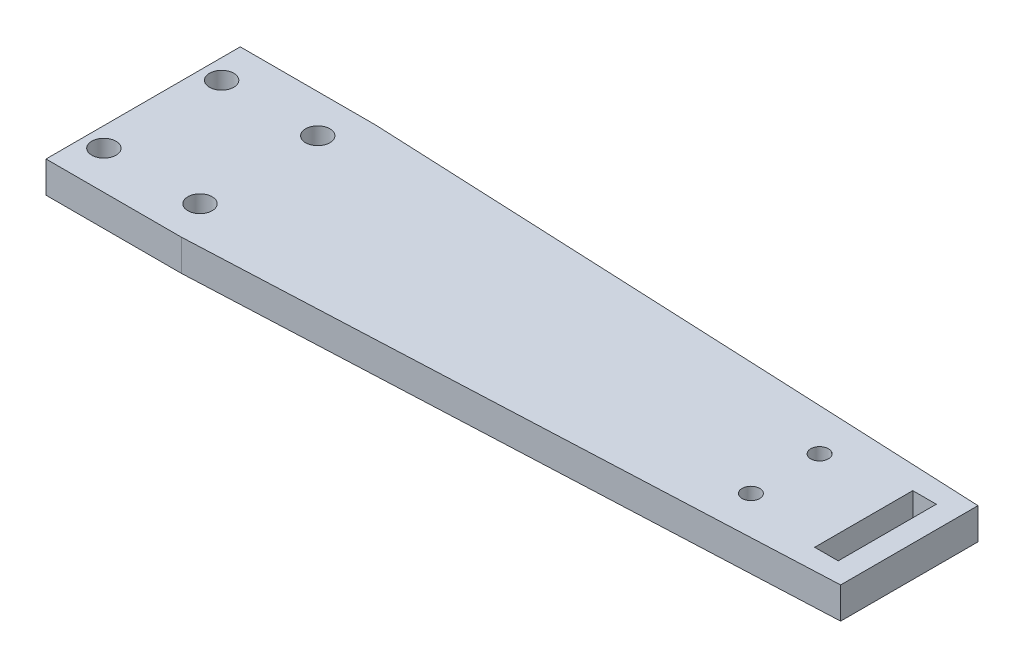
SolidWorks part; units mm, degrees
ref_plane "Front Plane" through (0, 0, 0) normal (0, 0, 1) x (1, 0, 0)
ref_plane "Top Plane" through (0, 0, 0) normal (0, 1, 0) x (1, 0, 0)
ref_plane "Right Plane" through (0, 0, 0) normal (1, 0, 0) x (0, 0, -1)
sketch "Sketch1" plane through (0, 0, 0) normal (0, 1, 0) x (1, 0, 0)
  line L1 (0, 0) -> (34.5, 0)
  line L2 (0, 0) -> (0, 49.5)
  line L3 (0, 49.5) -> (34.5, 49.5)
  line L4 (34.5, 0) -> (34.5, 49.5)
  dimension "D1" = 34.5
  dimension "D2" = 49.5
extrude "Boss-Extrude1" add sketch "Sketch1" along normal blind 8
sketch "Sketch2" plane through (0, 8, 0) normal (0, 1, 0) x (1, 0, 0)
  line L0 (34.5, 49.5) -> (0, 49.5) construction
  line L1 (0, 49.5) -> (0, 0) construction
  line L2 (17.25, 49.5) -> (17.25, 0) construction
  line L3 (0, 0) -> (34.5, 0) construction
  line L4 (0, 24.75) -> (17.25, 24.75) construction
  circle A0 centre (5, 39.75) radius 3.1
  circle A1 centre (5, 9.75) radius 3.1
  circle A2 centre (29.5, 9.75) radius 3.1
  circle A3 centre (29.5, 39.75) radius 3.1
  dimension "D1" = 6.2
  dimension "D3" = 5
  dimension "D2" = 9.75
extrude "Cut-Extrude1" cut sketch "Sketch2" against normal through all
sketch "Sketch3" plane through (0, 8, 0) normal (0, 1, 0) x (1, 0, 0)
  line L0 (17.25, 24.75) -> (181.75, 24.75) construction
  line L1 (195.25, 42.25) -> (34.5, 49.5)
  line L2 (195.25, 7.25) -> (34.5, 0)
  line L3 (195.25, 42.25) -> (195.25, 7.25)
  line L4 (176.5649, 14.4154) -> (94.6, 10.7187)
  line L6 (176.5649, 35.0846) -> (94.6, 38.7813)
  line L7 (34.5, 49.5) -> (34.5, 41.4919)
  line L8 (34.5, 0) -> (34.5, 49.5) construction
  line L9 (187.25, 34.6027) -> (34.1396, 41.5081) construction
  line L10 (34.5, 0) -> (34.5, 8.0081)
  line L11 (187.25, 14.8973) -> (34.1396, 7.9919) construction
  line L12 (89.6, 39.0068) -> (89.6, 10.4932)
  line L13 (94.6, 38.7813) -> (94.6, 10.7187)
  line L14 (94.6, 39.0068) -> (94.6, 10.4932) construction
  line L16 (0, 49.5) -> (0, 0) construction
  line L17 (0, 0) -> (34.5, 0) construction
  line L18 (89.6, 39.0068) -> (34.5, 41.4919)
  line L19 (89.6, 10.4932) -> (34.5, 8.0081)
  line L20 (176.5649, 35.0846) -> (176.5649, 14.4154)
  line L21 (187.25, 34.6027) -> (187.25, 14.8973) construction
  line L22 (183.63, 37.25) -> (189.63, 37.25)
  line L23 (183.63, 37.25) -> (183.63, 12.25)
  line L24 (183.63, 12.25) -> (189.63, 12.25)
  line L25 (189.63, 37.25) -> (189.63, 12.25)
  dimension "D1" = 17.5
  dimension "D4" = 17.25
  dimension "D5" = 24.75
  dimension "D6" = 17.5
  dimension "D7" = 178
  dimension "D8" = 25
  dimension "D9" = 12.5
  dimension "D10" = 6
  dimension "D11" = 5.62
  dimension "D2" = 8
  dimension "D3" = 5
extrude "Boss-Extrude2" add sketch "Sketch3" against normal through all
sketch "Sketch5" [suppressed] plane through (0, 5, 0) normal (0, 1, 0) x (1, 0, 0)
  line L0 (163.183, 43.1642) -> (163.183, 6.3358)
  line L1 (181.75, 42.25) -> (34.5, 49.5) construction
  line L2 (34.5, 0) -> (181.75, 7.25) construction
  line L3 (163.183, 6.3358) -> (181.75, 7.25)
  line L4 (181.75, 7.25) -> (181.75, 42.25)
  line L5 (181.75, 42.25) -> (163.183, 43.1642)
fillet "Fillet1" radius 10 6 edges at (94.6, 4, -10.7187) (94.6, 4, -38.7813) (89.6, 4, -10.4932) (89.6, 4, -39.0068) (34.5, 4, -41.4919) (34.5, 4, -8.0081)
fillet "Fillet2" radius 5 2 edges at (176.5649, 4, -14.4154) (176.5649, 4, -35.0846)
sketch "Sketch7" plane through (0, 8, 0) normal (0, 1, 0) x (1, 0, 0)
  line L4 (105.0505, 11.19) -> (171.7902, 14.2001)
  line L5 (94.6, 28.3201) -> (94.6, 21.1799)
  line L6 (171.7902, 35.2999) -> (105.0505, 38.31)
  line L7 (176.5649, 19.195) -> (176.5649, 30.305)
  line L8 (105.0505, 11.19) -> (171.7902, 14.2001)
  line L9 (94.6, 28.3201) -> (94.6, 21.1799)
  line L10 (171.7902, 35.2999) -> (105.0505, 38.31)
  line L11 (176.5649, 19.195) -> (176.5649, 30.305)
  line L12 (89.6, 20.0524) -> (89.6, 29.4476)
  line L13 (44.9506, 8.4795) -> (80.0505, 10.0625)
  line L14 (34.5, 31.0307) -> (34.5, 18.4693)
  line L15 (80.0505, 39.4375) -> (44.9506, 41.0205)
  line L16 (89.6, 20.0524) -> (89.6, 29.4476)
  line L17 (44.9506, 8.4795) -> (80.0505, 10.0625)
  line L18 (34.5, 31.0307) -> (34.5, 18.4693)
  line L19 (80.0505, 39.4375) -> (44.9506, 41.0205)
  arc A4 (94.6, 21.1799) -> (105.0505, 11.19) centre (104.6, 21.1799) ccw
  arc A5 (105.0505, 38.31) -> (94.6, 28.3201) centre (104.6, 28.3201) ccw
  arc A6 (176.5649, 30.305) -> (171.7902, 35.2999) centre (171.5649, 30.305) ccw
  arc A7 (171.7902, 14.2001) -> (176.5649, 19.195) centre (171.5649, 19.195) ccw
  arc A8 (94.6, 21.1799) -> (105.0505, 11.19) centre (104.6, 21.1799) ccw
  arc A9 (105.0505, 38.31) -> (94.6, 28.3201) centre (104.6, 28.3201) ccw
  arc A10 (176.5649, 30.305) -> (171.7902, 35.2999) centre (171.5649, 30.305) ccw
  arc A11 (171.7902, 14.2001) -> (176.5649, 19.195) centre (171.5649, 19.195) ccw
  arc A12 (80.0505, 10.0625) -> (89.6, 20.0524) centre (79.6, 20.0524) ccw
  arc A13 (34.5, 18.4693) -> (44.9506, 8.4795) centre (44.5, 18.4693) ccw
  arc A14 (44.9506, 41.0205) -> (34.5, 31.0307) centre (44.5, 31.0307) ccw
  arc A15 (89.6, 29.4476) -> (80.0505, 39.4375) centre (79.6, 29.4476) ccw
  arc A16 (80.0505, 10.0625) -> (89.6, 20.0524) centre (79.6, 20.0524) ccw
  arc A17 (34.5, 18.4693) -> (44.9506, 8.4795) centre (44.5, 18.4693) ccw
  arc A18 (44.9506, 41.0205) -> (34.5, 31.0307) centre (44.5, 31.0307) ccw
  arc A19 (89.6, 29.4476) -> (80.0505, 39.4375) centre (79.6, 29.4476) ccw
  dimension "D1" = 0
  dimension "D2" = 0
extrude "Boss-Extrude3" add sketch "Sketch7" against normal through all
sketch "Sketch8" plane through (0, 8, 0) normal (0, 1, 0) x (1, 0, 0)
  line L0 (183.63, 24.75) -> (163.63, 24.75) construction
  line L1 (183.63, 37.25) -> (183.63, 12.25) construction
  line L2 (163.63, 16) -> (163.63, 33.5) construction
  circle A0 centre (163.63, 33.5) radius 2.25
  circle A1 centre (163.63, 16) radius 2.25
  point P7 (163.63, 24.75)
  dimension "D3" = 4.5
  dimension "D4" = 4.5
  dimension "D1" = 17.5
  dimension "D2" = 20
extrude "Cut-Extrude2" cut sketch "Sketch8" against normal through all
